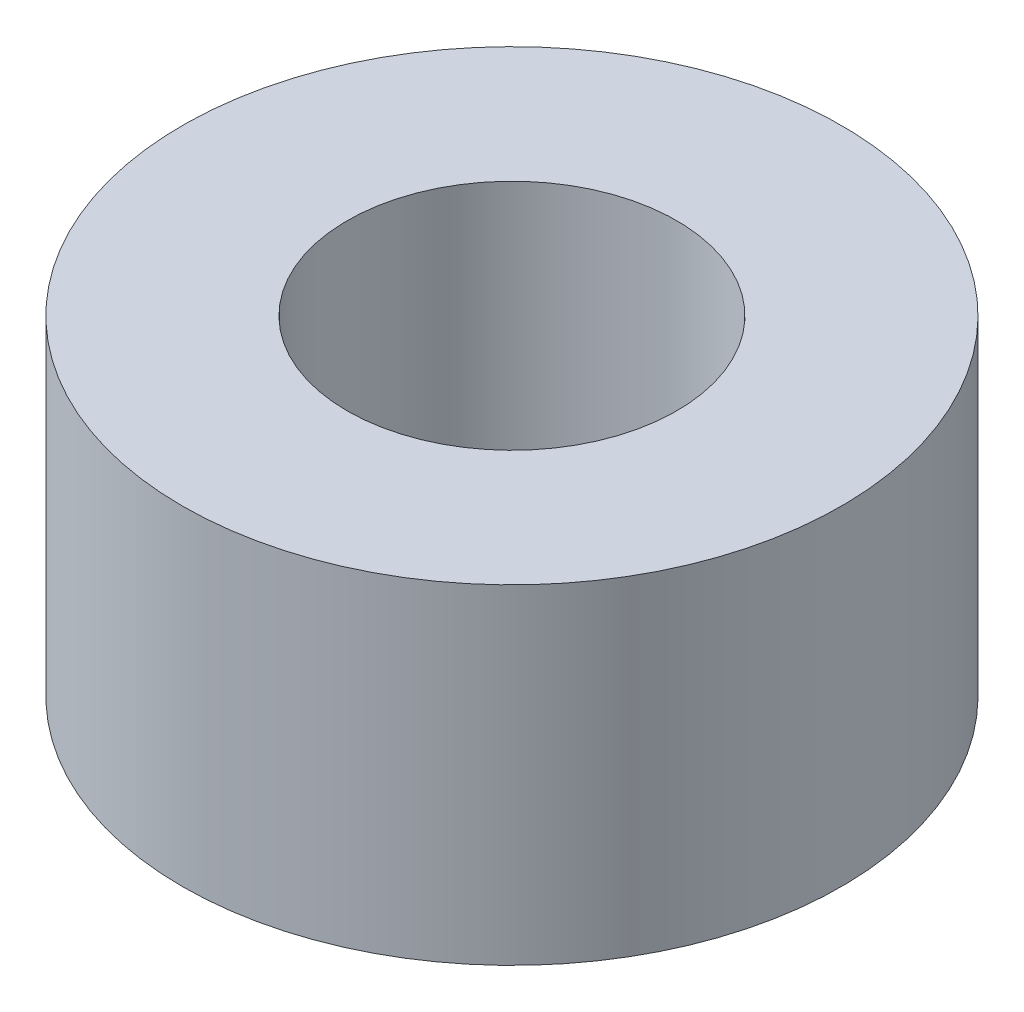
SolidWorks part; units mm, degrees
ref_plane "Plano frontal" through (0, 0, 0) normal (0, 0, 1) x (1, 0, 0)
ref_plane "Plano superior" through (0, 0, 0) normal (0, 1, 0) x (1, 0, 0)
ref_plane "Plano direito" through (0, 0, 0) normal (1, 0, 0) x (0, 0, -1)
sketch "Esboço1" plane through (0, 0, 0) normal (0, 1, 0) x (1, 0, 0)
  circle A0 centre (0, 0) radius 3
  circle A1 centre (0, 0) radius 1.5
  dimension "D1" = 6
  dimension "D2" = 3
extrude "Ressalto-extrusão1" add sketch "Esboço1" along normal blind 3
